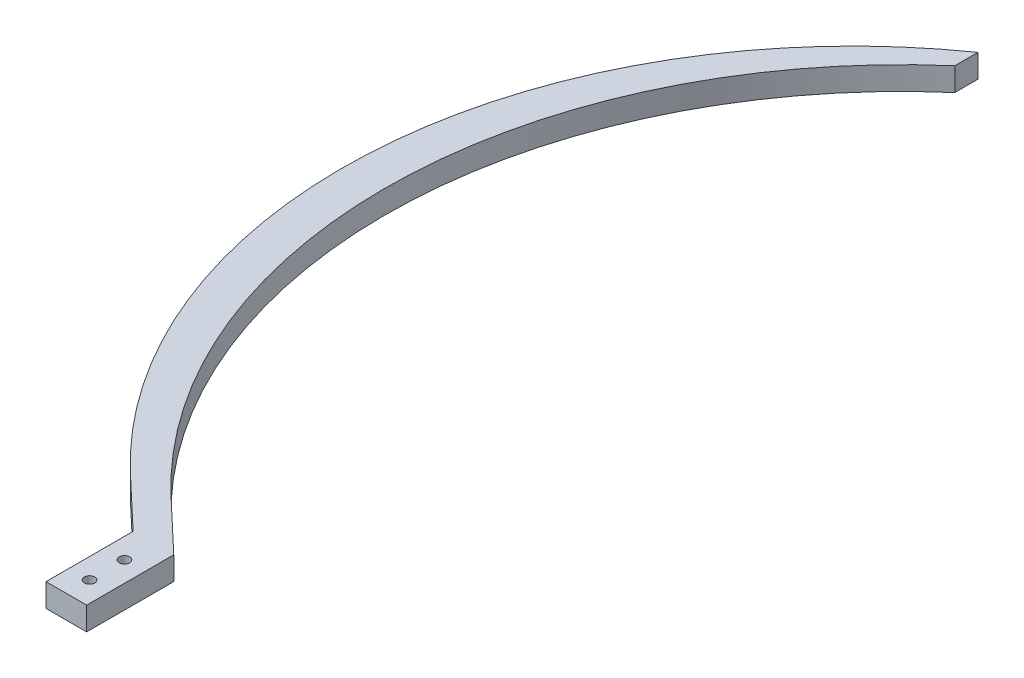
SolidWorks part; units mm, degrees
ref_plane "前视基准面" through (0, 0, 0) normal (0, 0, 1) x (1, 0, 0)
ref_plane "上视基准面" through (0, 0, 0) normal (0, 1, 0) x (1, 0, 0)
ref_plane "右视基准面" through (0, 0, 0) normal (1, 0, 0) x (0, 0, -1)
sketch "草图1" plane through (0, 0, 0) normal (0, 1, 0) x (1, 0, 0)
  line L2 (3.5, 7.5) -> (3.5, -7.5)
  line L3 (3.5, -7.5) -> (-3.5, -7.5)
  line L4 (-3.5, 7.5) -> (-3.5, -7.5)
  line L5 (0, -7.5) -> (0, 3.5) construction
  line L6 (3.5, 0) -> (-3.5, 0) construction
  line L12 (3.5, 7.5) -> (-5.2099, 15.7545)
  line L13 (-3.5, 7.5) -> (-12.2099, 15.7545)
  line L14 (-2.1878, 151.6871) -> (-2.1878, 147.6871)
  arc A10 (-5.2099, 15.7545) -> (-2.1878, 147.6871) centre (56.0112, 80.3531) cw
  arc A11 (-12.2099, 15.7545) -> (-2.1878, 151.6871) centre (48.3234, 79.6272) cw
  point P0 (0, 0)
  dimension "D3" = 89
  dimension "D4" = 88
  dimension "D5" = 12
  dimension "D6" = 12
  dimension "D7" = 180
  dimension "D1" = 7
  dimension "D2" = 4
  dimension "D10" = 15
extrude "凸台-拉伸1" add sketch "草图1" along normal blind 4
sketch "草图5" plane through (0, 4, 0) normal (0, 1, 0) x (1, 0, 0)
  line L0 (3.5, -7.5) -> (-3.5, -7.5) construction
  circle A0 centre (0, -3.5) radius 0.9
  circle A1 centre (0, 2.5) radius 0.9
  dimension "D1" = 1.8
  dimension "D2" = 1.8
  dimension "D3" = 4
  dimension "D4" = 6
extrude "切除-拉伸1" cut sketch "草图5" against normal blind 10 contours A0 | A1
